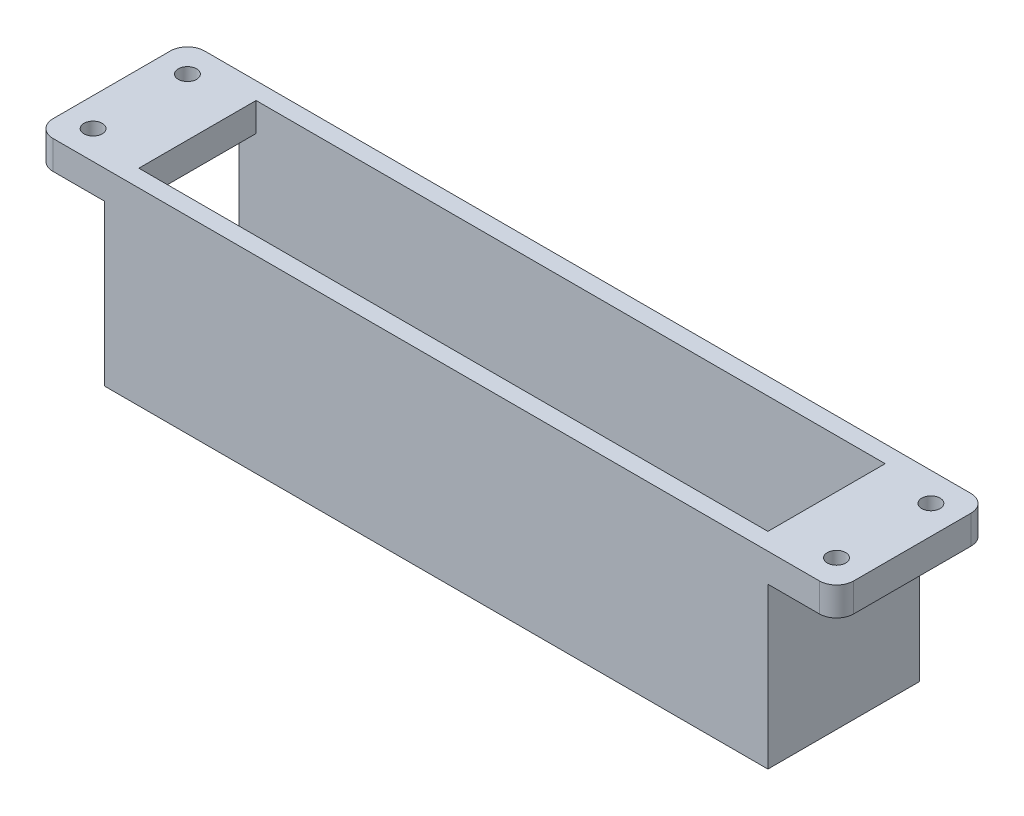
SolidWorks part; units mm, degrees
ref_plane "Płaszczyzna przednia" through (0, 0, 0) normal (0, 0, 1) x (1, 0, 0)
ref_plane "Płaszczyzna górna" through (0, 0, 0) normal (0, 1, 0) x (1, 0, 0)
ref_plane "Płaszczyzna prawa" through (0, 0, 0) normal (1, 0, 0) x (0, 0, -1)
sketch "Szkic1" plane through (0, 0, 0) normal (0, 0, 1) x (1, 0, 0)
  line L1 (0, 0) -> (116, 0)
  line L2 (0, 0) -> (0, 28)
  line L4 (116, 0) -> (116, 28)
  line L5 (-12, 33) -> (-12, 28)
  line L6 (-12, 28) -> (0, 28)
  line L8 (128, 33) -> (128, 28)
  line L9 (128, 28) -> (116, 28)
  line L10 (128, 33) -> (-12, 33)
  dimension "D1" = 116
  dimension "D2" = 140
  dimension "D4" = 28
  dimension "D5" = 5
  dimension "D6" = 5
extrude "Dodanie-wyciągnięcie1" add sketch "Szkic1" along normal blind 26.5
sketch "Szkic2" plane through (0, 33, 0) normal (0, 1, 0) x (1, 0, 0)
  line L0 (128, 0) -> (-12, 0) construction
  line L1 (3, -3) -> (113, -3)
  line L2 (3, -3) -> (3, -23.5)
  line L3 (3, -23.5) -> (113, -23.5)
  line L4 (113, -3) -> (113, -23.5)
  line L5 (3, -3) -> (3, 0) construction
  line L6 (58, 0) -> (58, -26.5) construction
  line L7 (128, -26.5) -> (-12, -26.5) construction
  line L8 (58, -3) -> (58, -23.5) construction
  line L9 (3, -23.5) -> (3, -26.5) construction
  dimension "D1" = 20.5
  dimension "D2" = 110
extrude "Wytnij-wyciągnięcie1" cut sketch "Szkic2" against normal offset from surface (30 mm away) 3 up to face at (58, 0, 13.25)
sketch "Szkic4" plane through (0, 0, 0) normal (-1, 0, 0) x (0, 0, 1)
  line L0 (26.5, 0) -> (0, 0) construction
  line L1 (3, 28) -> (23.5, 28)
  line L2 (3, 28) -> (3, 3)
  line L3 (3, 3) -> (23.5, 3)
  line L4 (23.5, 28) -> (23.5, 3)
  line L5 (0, 28) -> (0, 0) construction
  line L6 (26.5, 28) -> (0, 28) construction
  point P8 (3, 28)
  dimension "D1" = 20.5
  dimension "D3" = 3
  dimension "D4" = 3
extrude "Wytnij-wyciągnięcie3" cut sketch "Szkic4" against normal blind 3
sketch "Szkic5" plane through (0, 33, 0) normal (0, 1, 0) x (1, 0, 0)
  line L0 (128, 0) -> (-12, 0) construction
  line L1 (-12, -26.5) -> (-12, 0) construction
  line L2 (128, -26.5) -> (128, 0) construction
  line L3 (128, -26.5) -> (-12, -26.5) construction
  circle A0 centre (-7, -5) radius 1.6
  circle A1 centre (123, -5) radius 1.6
  circle A2 centre (123, -21.5) radius 1.6
  circle A3 centre (-7, -21.5) radius 1.6
  dimension "D1" = 3.2
  dimension "D3" = 5
  dimension "D6" = 5
  dimension "D7" = 5
  dimension "D8" = 5
  dimension "D2" = 5
  dimension "D4" = 2
  dimension "D5" = 2
extrude "Wytnij-wyciągnięcie4" cut sketch "Szkic5" against normal through all
fillet "Fillet1" radius 3 4 edges at (128, 30.5, 0) (128, 30.5, 26.5) (-12, 30.5, 0) (-12, 30.5, 26.5)
